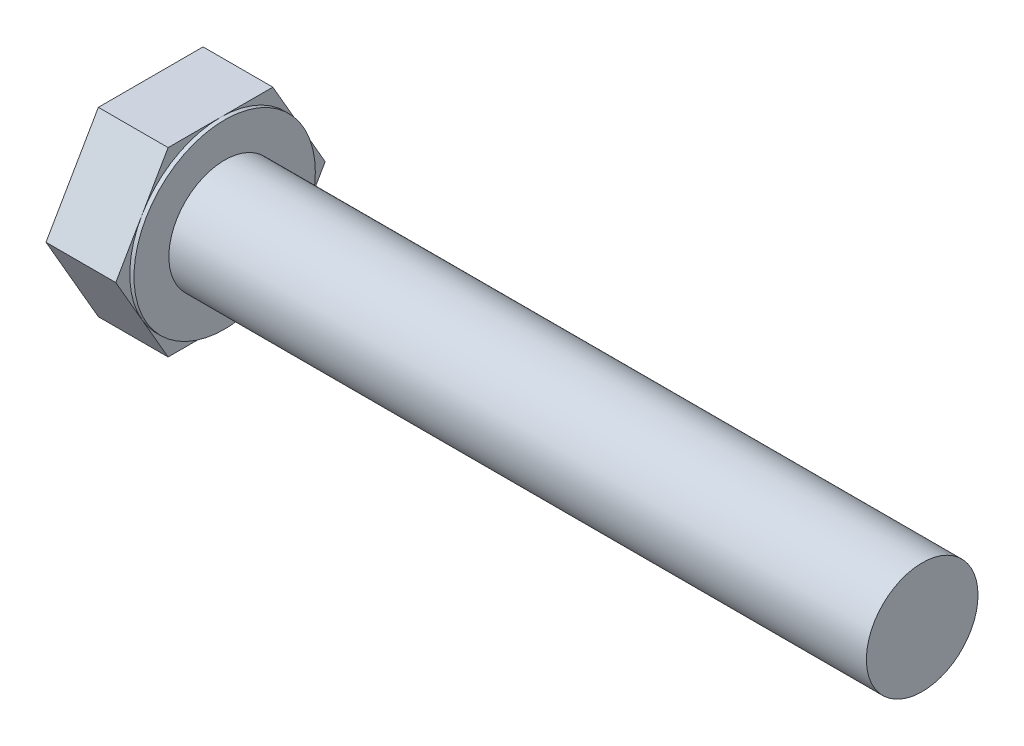
SolidWorks part; units mm, degrees
material "Plain Carbon Steel"
ref_plane "Front Plane" through (0, 0, 0) normal (0, 0, 1) x (1, 0, 0)
ref_plane "Top Plane" through (0, 0, 0) normal (0, 1, 0) x (1, 0, 0)
ref_plane "Right Plane" through (0, 0, 0) normal (1, 0, 0) x (0, 0, -1)
sketch "Sketch1" plane through (0, 0, 0) normal (1, 0, 0) x (0, 0, -1)
  line L1 (-7.5056, 0) -> (-3.7528, -6.5)
  line L2 (-3.7528, -6.5) -> (3.7528, -6.5)
  line L3 (3.7528, -6.5) -> (7.5056, 0)
  line L4 (7.5056, 0) -> (3.7528, 6.5)
  line L5 (3.7528, 6.5) -> (-3.7528, 6.5)
  line L6 (-3.7528, 6.5) -> (-7.5056, 0)
  circle A0 centre (0, 0) radius 6.5 construction
  dimension "D1" = 13
extrude "Boss-Extrude1" add sketch "Sketch1" against normal blind 5
sketch "Sketch2" plane through (0, 0, 0) normal (1, 0, 0) x (0, 0, -1)
  line L0 (3.7528, 6.5) -> (-3.7528, 6.5) construction
  circle A0 centre (0, 0) radius 6.5
extrude "Boss-Extrude2" add sketch "Sketch2" along normal blind 0.3
sketch "Sketch3" plane through (0.3, 0, 0) normal (1, 0, 0) x (0, 0, -1)
  circle A0 centre (0, 0) radius 4
  dimension "D1" = 8
extrude "Boss-Extrude3" add sketch "Sketch3" along normal blind 50
